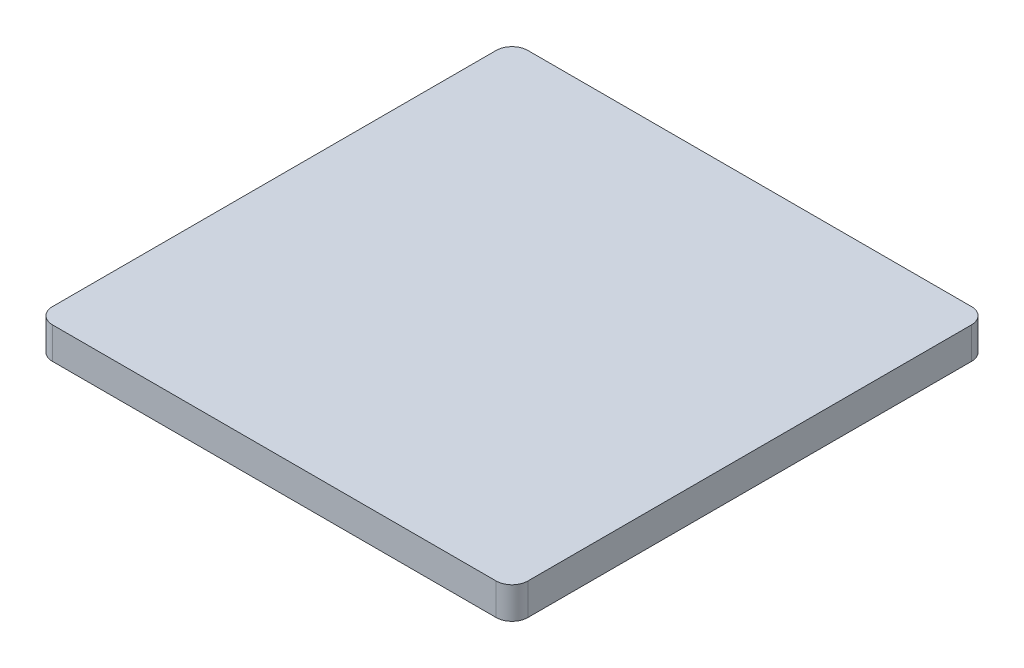
SolidWorks part; units mm, degrees
ref_plane "Alzado" through (0, 0, 0) normal (0, 0, 1) x (1, 0, 0)
ref_plane "Planta" through (0, 0, 0) normal (0, 1, 0) x (1, 0, 0)
ref_plane "Vista lateral" through (0, 0, 0) normal (1, 0, 0) x (0, 0, -1)
sketch "Croquis1" plane through (0, 0, 0) normal (0, 1, 0) x (1, 0, 0)
  line L1 (15, -15) -> (-15, -15)
  line L2 (15, -15) -> (15, 15)
  line L3 (15, 15) -> (-15, 15)
  line L4 (-15, -15) -> (-15, 15)
  line L5 (15, -15) -> (-15, 15) construction
  line L6 (15, 15) -> (-15, -15) construction
  point P0 (0, 0)
  dimension "D1" = 30
extrude "Extruir1" add sketch "Croquis1" along normal blind 2
fillet "Redondeo1" radius 1 4 edges at (-15, 1, -15) (15, 1, -15) (15, 1, 15) (-15, 1, 15)
